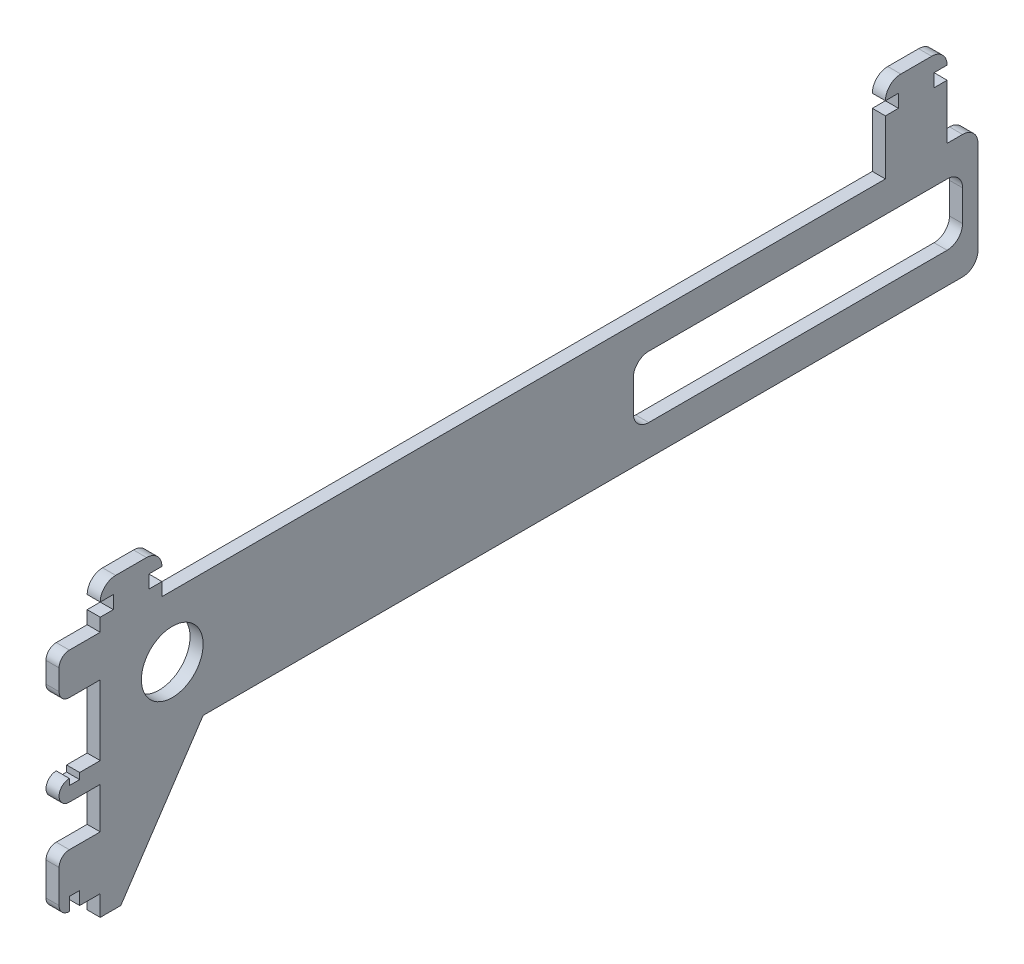
SolidWorks part; units mm, degrees
other "Markup1"
sketch "Sketch2" plane through (3.175, -45, -103.505) normal (0.9862, -0.086, -0.1416) x (-0.158, -0.2305, -0.9602)
other "Markup2"
sketch "Sketch3" plane through (3.175, -45, -103.505) normal (0.9862, -0.086, -0.1416) x (-0.158, -0.2305, -0.9602)
ref_plane "Front Plane" through (0, 0, 0) normal (0, 0, 1) x (1, 0, 0)
ref_plane "Top Plane" through (0, 0, 0) normal (0, 1, 0) x (1, 0, 0)
ref_plane "Right Plane" through (0, 0, 0) normal (1, 0, 0) x (0, 0, -1)
sketch "Sketch1" plane through (0, 0, 0) normal (1, 0, 0) x (0, 0, -1)
  line L1 (-99.755, 15) -> (99.755, 15)
  line L3 (-84.755, -15) -> (99.755, -15)
  line L5 (99.755, 3.75) -> (99.755, -3.75)
  line L6 (96.005, 7.5) -> (96.005, 15)
  line L7 (99.755, 0) -> (99.755, 3.75)
  line L8 (99.755, 0) -> (99.755, 3.75)
  line L9 (99.755, 0) -> (99.755, -3.75)
  line L10 (96.005, 7.5) -> (23.505, 7.5)
  line L12 (23.505, -7.5) -> (96.005, -7.5)
  line L13 (19.755, 0) -> (19.755, 3.75)
  line L14 (19.755, 0) -> (19.755, -3.75)
  line L15 (-109.755, 15) -> (-94.755, 15)
  line L17 (103.505, 11.25) -> (103.505, -11.25)
  line L18 (-109.755, 15) -> (-109.755, 18.175)
  line L19 (-109.755, 18.175) -> (-94.755, 18.175)
  line L23 (-109.755, 0) -> (-109.755, 15)
  line L24 (-109.755, 0) -> (-109.755, -15)
  line L25 (-109.755, -15) -> (-109.755, -45)
  line L26 (-109.755, -45) -> (-104.755, -45)
  line L27 (-104.755, -45) -> (-84.755, -15)
  line L28 (-109.755, 15) -> (-99.755, 15)
  line L29 (-94.755, 18.175) -> (-94.755, 15)
  line L31 (-109.755, 18.175) -> (-106.58, 18.175)
  line L32 (-94.755, 18.175) -> (-97.93, 18.175)
  line L33 (-106.58, 18.175) -> (-106.58, 21.35)
  line L34 (-106.58, 21.35) -> (-97.93, 21.35)
  line L35 (-97.93, 21.35) -> (-97.93, 18.175)
  line L36 (-102.255, 21.35) -> (-109.755, 21.35)
  line L37 (-102.255, 21.35) -> (-94.755, 21.35)
  line L38 (-102.255, 21.35) -> (-94.755, 21.35)
  line L39 (96.005, 25.1) -> (96.005, 15)
  line L40 (96.005, 15) -> (81.005, 15)
  line L41 (81.005, 15) -> (81.005, 25.1)
  line L42 (81.005, 25.1) -> (81.005, 28.275)
  line L43 (81.005, 28.275) -> (96.005, 28.275)
  line L44 (96.005, 28.275) -> (96.005, 25.1)
  line L45 (81.005, 28.275) -> (84.18, 28.275)
  line L46 (96.005, 28.275) -> (92.83, 28.275)
  line L47 (84.18, 28.275) -> (84.18, 31.45)
  line L48 (84.18, 31.45) -> (92.83, 31.45)
  line L49 (92.83, 31.45) -> (92.83, 28.275)
  line L50 (84.18, 31.45) -> (81.005, 31.45)
  line L51 (81.005, 31.45) -> (88.505, 31.45)
  line L52 (88.505, 31.45) -> (96.005, 31.45)
  line L53 (96.005, 31.45) -> (88.505, 31.45)
  line L54 (92.255, 35.2) -> (84.755, 35.2)
  line L55 (-109.755, 15) -> (-109.755, 18.175)
  line L56 (-106.005, 25.1) -> (-98.505, 25.1)
  line L57 (-109.755, 15) -> (-109.755, 5)
  line L58 (-109.755, 15) -> (-117.255, 15)
  line L59 (-119.755, 12.5) -> (-119.755, 7.5)
  line L60 (-117.255, 5) -> (-109.755, 5)
  line L61 (-113.505, 15) -> (-117.255, 15)
  line L62 (-109.755, -45) -> (-109.755, -40)
  line L63 (-109.755, -40) -> (-109.755, -27)
  line L64 (-109.755, -27) -> (-117.255, -27)
  line L66 (-114.755, -40) -> (-109.755, -40)
  line L67 (-109.755, -27) -> (-109.755, -17)
  line L68 (-109.755, -17) -> (-109.755, -12)
  line L69 (-109.755, -12) -> (-114.755, -12)
  line L70 (-117.255, -12) -> (-117.255, -13.5)
  line L71 (-117.255, -17) -> (-109.755, -17)
  line L74 (-117.255, -40) -> (-117.255, -37.5)
  line L75 (-119.755, -37.5) -> (-119.755, -29.5)
  line L76 (-117.255, -12) -> (-117.255, -13.5)
  line L77 (-117.255, -40) -> (-117.255, -36.825)
  line L78 (-117.255, -36.825) -> (-114.755, -36.825)
  line L79 (-114.755, -36.825) -> (-114.755, -40)
  line L80 (-117.255, -12) -> (-117.255, -13.5)
  line L81 (-117.255, -13.5) -> (-114.755, -13.5)
  line L82 (-114.755, -13.5) -> (-114.755, -12)
  line L83 (-117.255, -36.825) -> (-117.255, -40)
  circle A1 centre (-92.255, 0) radius 7.5
  arc A2 (19.755, 3.75) -> (23.505, 7.5) centre (23.505, 3.75) cw
  arc A3 (19.755, -3.75) -> (23.505, -7.5) centre (23.505, -3.75) ccw
  arc A4 (99.755, -3.75) -> (96.005, -7.5) centre (96.005, -3.75) cw
  arc A5 (99.755, 3.75) -> (96.005, 7.5) centre (96.005, 3.75) ccw
  arc A6 (99.755, 15) -> (103.505, 11.25) centre (99.755, 11.25) cw
  arc A7 (99.755, -15) -> (103.505, -11.25) centre (99.755, -11.25) ccw
  arc A8 (-109.755, 21.35) -> (-106.005, 25.1) centre (-106.005, 21.35) cw
  arc A9 (-94.755, 21.35) -> (-98.505, 25.1) centre (-98.505, 21.35) ccw
  arc A10 (81.005, 31.45) -> (84.755, 35.2) centre (84.755, 31.45) cw
  arc A11 (96.005, 31.45) -> (92.255, 35.2) centre (92.255, 31.45) ccw
  arc A12 (-117.255, 15) -> (-119.755, 12.5) centre (-117.255, 12.5) ccw
  arc A13 (-117.255, 5) -> (-119.755, 7.5) centre (-117.255, 7.5) cw
  arc A14 (-117.255, -27) -> (-119.755, -29.5) centre (-117.255, -29.5) ccw
  arc A15 (-117.255, -40) -> (-119.755, -37.5) centre (-117.255, -37.5) cw
  arc A16 (-117.255, -12) -> (-117.255, -17) centre (-117.255, -14.5) ccw
  point P0 (0, 0)
  point P39 (-96.58, 18.175)
  point P40 (-109.755, 0)
extrude "Boss-Extrude1" add sketch "Sketch1" along normal blind 3.175
